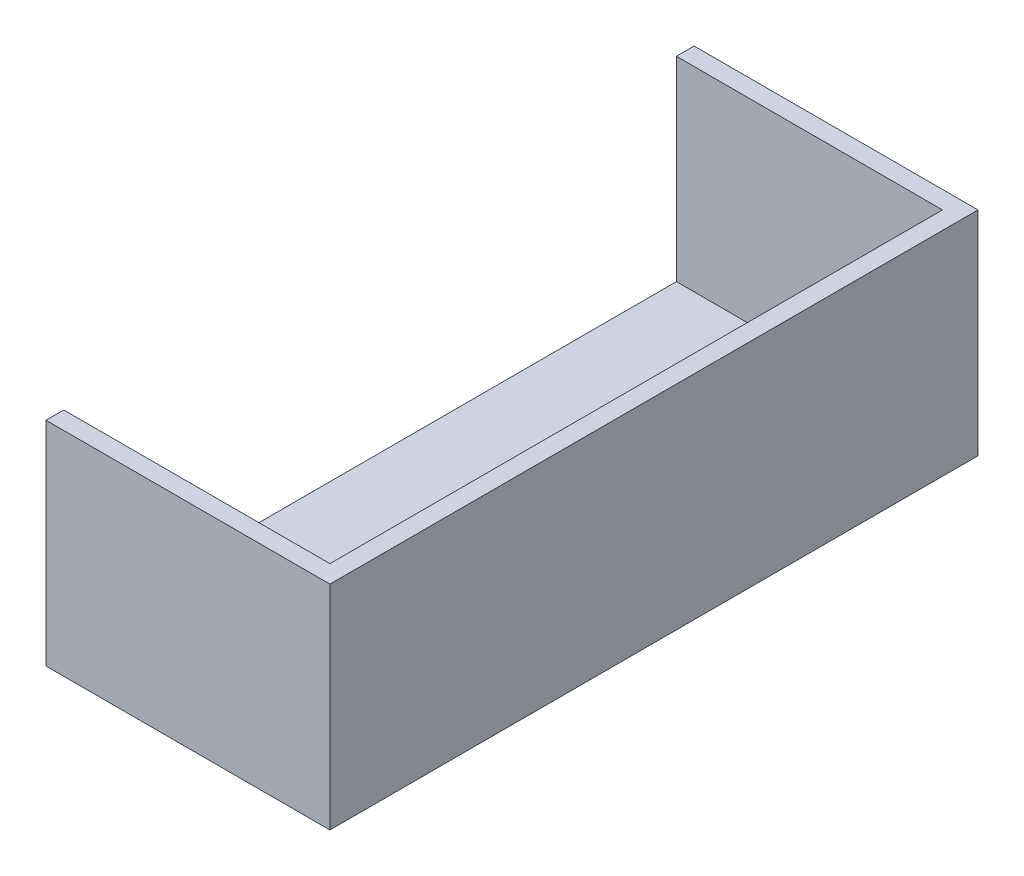
SolidWorks part; units mm, degrees
ref_plane "Front Plane" through (0, 0, 0) normal (0, 0, 1) x (1, 0, 0)
ref_plane "Top Plane" through (0, 0, 0) normal (0, 1, 0) x (1, 0, 0)
ref_plane "Right Plane" through (0, 0, 0) normal (1, 0, 0) x (0, 0, -1)
sketch "Sketch1" plane through (0, 0, 0) normal (0, 0, 1) x (1, 0, 0)
  line L5 (12.7, 9.525) -> (-12.7, 9.525)
  line L6 (12.7, 9.525) -> (12.7, -9.525)
  line L7 (12.7, -9.525) -> (-12.7, -9.525)
  line L8 (-12.7, 9.525) -> (-12.7, -9.525)
  line L9 (12.7, 9.525) -> (-12.7, -9.525) construction
  line L10 (12.7, -9.525) -> (-12.7, 9.525) construction
  point P0 (0, 0)
  dimension "D1" = 25.4
  dimension "D2" = 19.05
extrude "Boss-Extrude2" add sketch "Sketch1" along normal blind 57.9882
sketch "Sketch4" plane through (-12.7, 0, 0) normal (-1, 0, 0) x (0, 0, 1)
  line L0 (1.5875, 9.525) -> (1.5875, -7.9375)
  line L1 (57.9882, 9.525) -> (0, 9.525) construction
  line L2 (1.5875, -7.9375) -> (56.4007, -7.9375)
  line L3 (56.4007, -7.9375) -> (56.4007, 9.525)
  line L4 (0, 9.525) -> (0, -9.525) construction
  line L5 (57.9882, -9.525) -> (0, -9.525) construction
  line L6 (57.9882, 9.525) -> (57.9882, -9.525) construction
  line M7 (57.9882, 9.525) -> (0, 9.525)
  dimension "D1" = 1.5875
  dimension "D2" = 1.5875
  dimension "D3" = 1.5875
extrude "Cut-Extrude3" cut sketch "Sketch4" against normal blind 23.8125 and the other way through all contours L2 L3 L0 M7
sketch "Sketch5" plane through (0, -7.9375, 0) normal (0, 1, 0) x (1, 0, 0)
  line L0 (-12.7, -1.5875) -> (-12.7, -56.4007) construction
  line L1 (12.7, -57.9882) -> (-12.7, -57.9882) construction
  line L2 (-12.7, -1.5875) -> (11.1125, -1.5875) construction
  circle A0 centre (0, -10.0542) radius 4.0767
  circle A1 centre (0, -49.5215) radius 4.0767
  dimension "D1" = 8.1534
  dimension "D2" = 8.1534
  dimension "D3" = 12.7
  dimension "D4" = 8.4667
  dimension "D5" = 8.4667
  dimension "D6" = 12.7
extrude "Cut-Extrude4" cut sketch "Sketch5" against normal blind 23.8125
